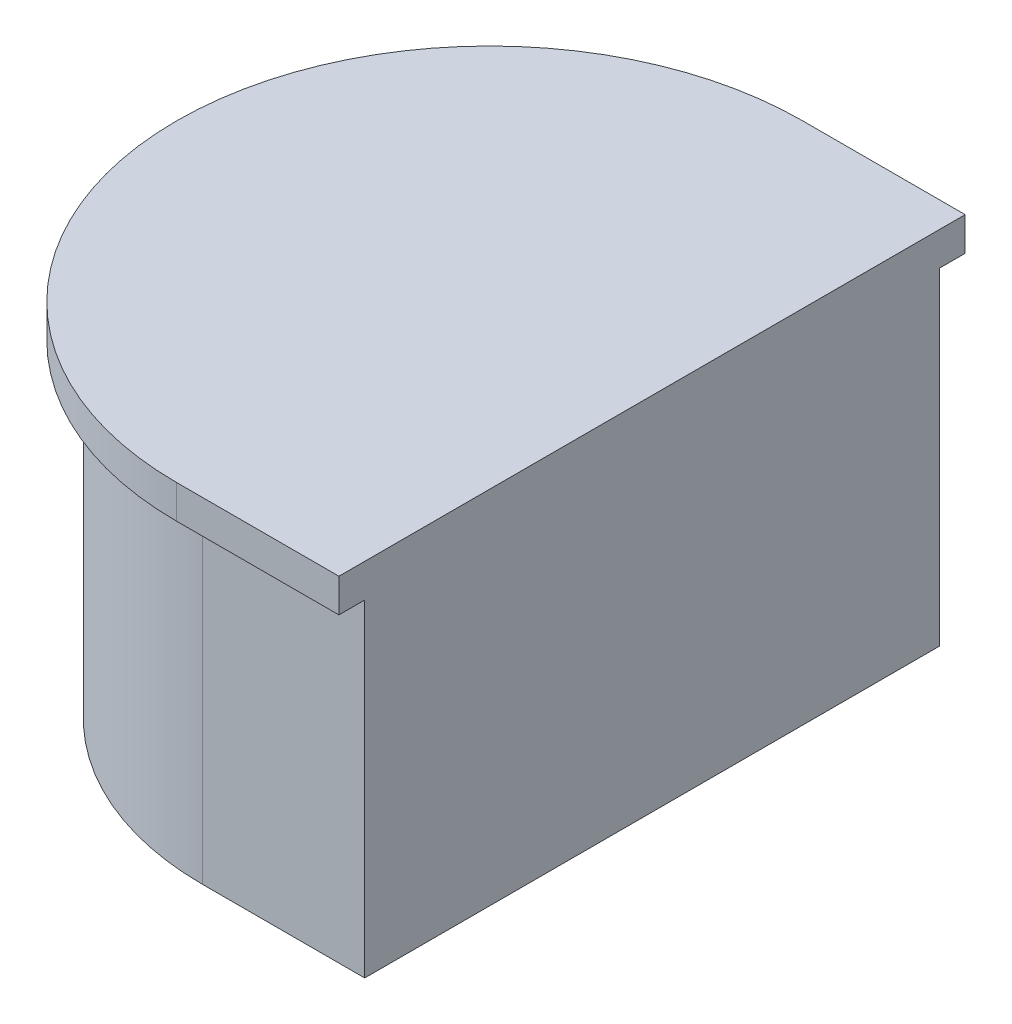
SolidWorks part; units mm, degrees
ref_plane "Front Plane" through (0, 0, 0) normal (0, 0, 1) x (1, 0, 0)
ref_plane "Top Plane" through (0, 0, 0) normal (0, 1, 0) x (1, 0, 0)
ref_plane "Right Plane" through (0, 0, 0) normal (1, 0, 0) x (0, 0, -1)
sketch "Sketch1" plane through (0, 0, 0) normal (0, 1, 0) x (1, 0, 0)
  line L12 (5.3798, -23.2189) -> (17.981, -23.2189)
  line L19 (17.981, 21.3766) -> (5.3798, 21.3766)
  line L28 (17.981, 21.3766) -> (17.981, -23.2189)
  arc A2 (5.3798, 21.3766) -> (5.3798, -23.2189) centre (5.3798, -0.9211) ccw
extrude "Boss-Extrude1" add sketch "Sketch1" along normal blind 28
sketch "Sketch2" plane through (0, 28, 0) normal (0, 1, 0) x (1, 0, 0)
  line L5 (5.3798, -25.2189) -> (17.981, -25.2189)
  line L6 (17.981, 23.3766) -> (5.3798, 23.3766)
  line L7 (5.3798, -25.2189) -> (17.981, -25.2189)
  line L8 (17.981, 23.3766) -> (5.3798, 23.3766)
  line L10 (17.981, 23.3766) -> (17.981, 21.3766)
  line L11 (17.981, -23.2189) -> (17.981, -25.2189)
  line L13 (17.981, -23.2189) -> (17.981, 21.3766)
  line L14 (17.981, 21.3766) -> (5.3798, 21.3766)
  line L15 (5.3798, -23.2189) -> (17.981, -23.2189)
  line L17 (17.981, 21.3766) -> (5.3798, 21.3766)
  line L18 (5.3798, -23.2189) -> (17.981, -23.2189)
  arc A4 (5.3798, 23.3766) -> (5.3798, -25.2189) centre (5.3798, -0.9211) ccw
  arc A5 (5.3798, 23.3766) -> (5.3798, -25.2189) centre (5.3798, -0.9211) ccw
  arc A7 (5.3798, 21.3766) -> (5.3798, -23.2189) centre (5.3798, -0.9211) ccw
  arc A8 (5.3798, 21.3766) -> (5.3798, -23.2189) centre (5.3798, -0.9211) ccw
  dimension "D1" = 2
  dimension "D2" = 0
extrude "Boss-Extrude2" add sketch "Sketch2" against normal blind 2.6
